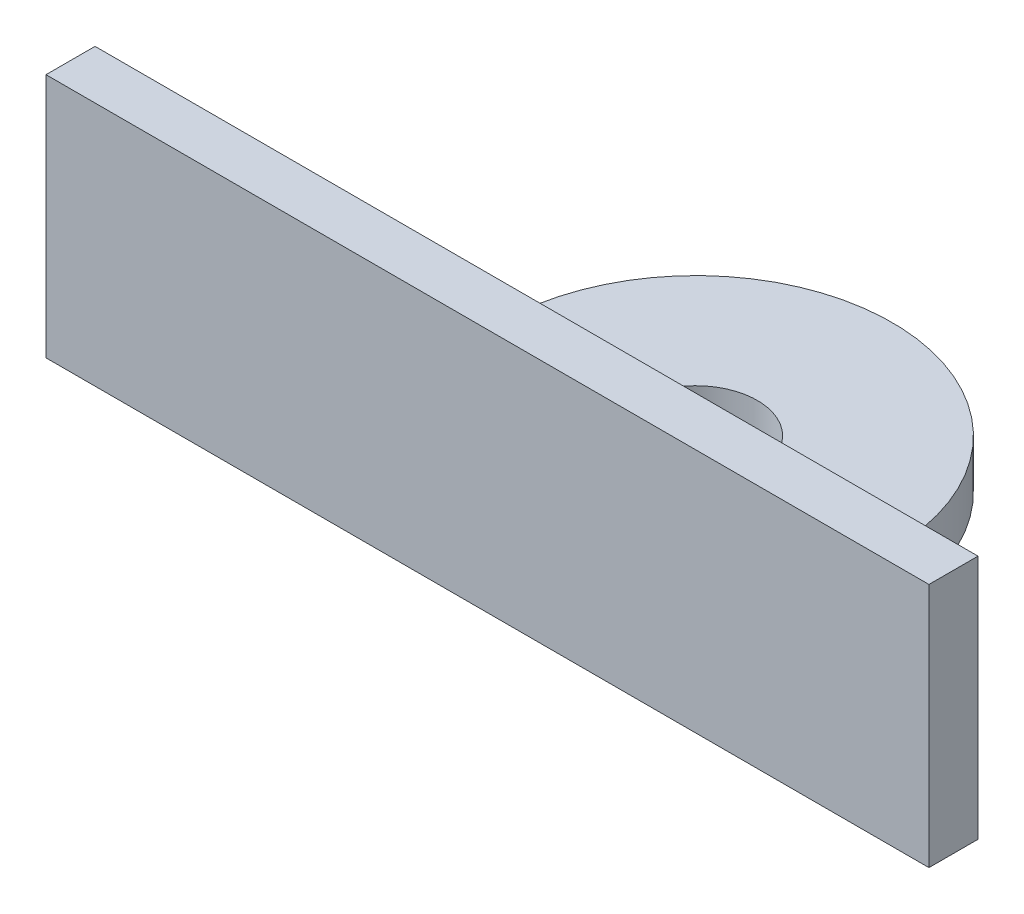
SolidWorks part; units mm, degrees
ref_plane "Alzado" through (0, 0, 0) normal (0, 0, 1) x (1, 0, 0)
ref_plane "Planta" through (0, 0, 0) normal (0, 1, 0) x (1, 0, 0)
ref_plane "Vista lateral" through (0, 0, 0) normal (1, 0, 0) x (0, 0, -1)
sketch "Sketch1" plane through (0, 0, 0) normal (0, 1, 0) x (1, 0, 0)
  line L0 (-40, 0) -> (40, 0)
  line L1 (40, 0) -> (40, 42.5)
  line L2 (-40, 42.5) -> (-40, 0)
  arc A0 (40, 42.5) -> (-40, 42.5) centre (0, 42.5) ccw
  circle A2 centre (0, 42.5) radius 12.5
  point P5 (0, 0)
  point P8 (0, 0)
  dimension "D1" = 25
  dimension "D2" = 30
  dimension "D3" = 80
extrude "Boss-Extrude1" add sketch "Sketch1" along normal blind 10
sketch "Sketch2" plane through (0, 0, 0) normal (0, 0, 1) x (1, 0, 0)
  line L0 (-40, 10) -> (-40, 0) construction
  line L1 (-90, 0) -> (90, 0)
  line L2 (-90, 0) -> (-90, 50)
  line L3 (-90, 50) -> (90, 50)
  line L4 (90, 0) -> (90, 50)
  point P4 (0, 50)
  point P6 (0, 0)
  dimension "D1" = 50
  dimension "D2" = 50
extrude "Boss-Extrude2" add sketch "Sketch2" against normal blind 10
